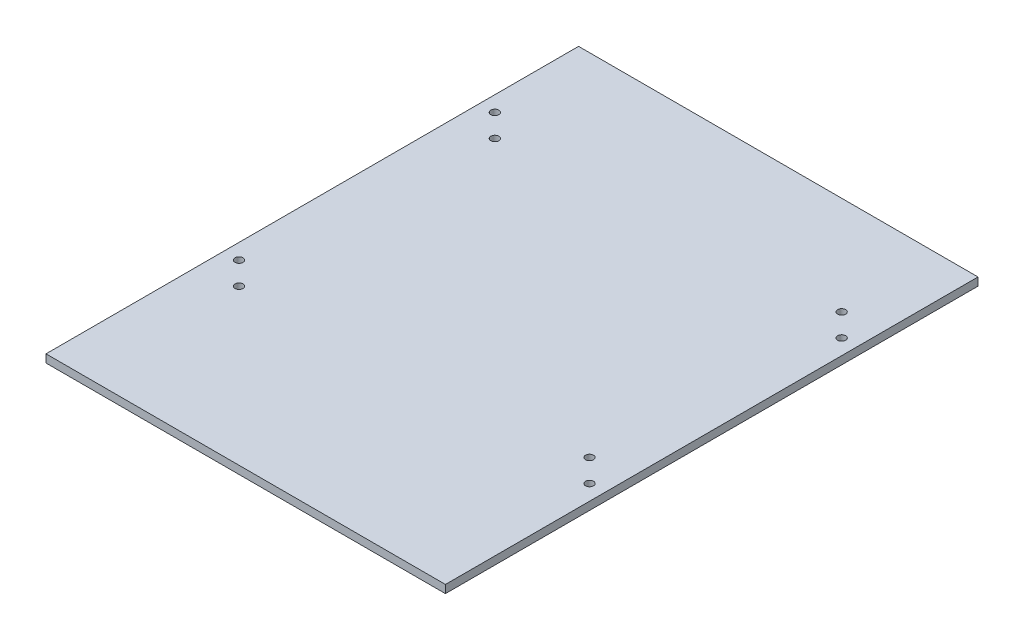
SolidWorks part; units mm, degrees
ref_plane "Front Plane" through (0, 0, 0) normal (0, 0, 1) x (1, 0, 0)
ref_plane "Top Plane" through (0, 0, 0) normal (0, 1, 0) x (1, 0, 0)
ref_plane "Right Plane" through (0, 0, 0) normal (1, 0, 0) x (0, 0, -1)
sketch "Sketch1" plane through (0, 0, 0) normal (0, 1, 0) x (1, 0, 0)
  line L1 (-75, -100) -> (75, -100)
  line L2 (-75, -100) -> (-75, 100)
  line L3 (-75, 100) -> (75, 100)
  line L4 (75, -100) -> (75, 100)
  line L5 (-75, -100) -> (75, 100) construction
  line L6 (-75, 100) -> (75, -100) construction
  circle A0 centre (-69.2426, 62.7961) radius 1.5
  circle A1 centre (-60.7574, 54.3108) radius 1.5
  circle A2 centre (60.7574, 63.0348) radius 1.5
  circle A3 centre (69.2426, 54.5495) radius 1.5
  circle A4 centre (-69.2426, -33.2742) radius 1.5
  circle A5 centre (-60.7574, -41.7595) radius 1.5
  circle A6 centre (60.7574, -31.6419) radius 1.5
  circle A7 centre (69.2426, -40.1271) radius 1.5
  point P0 (0, 0)
  dimension "D1" = 150
  dimension "D2" = 200
extrude "Boss-Extrude1" add sketch "Sketch1" along normal blind 3
